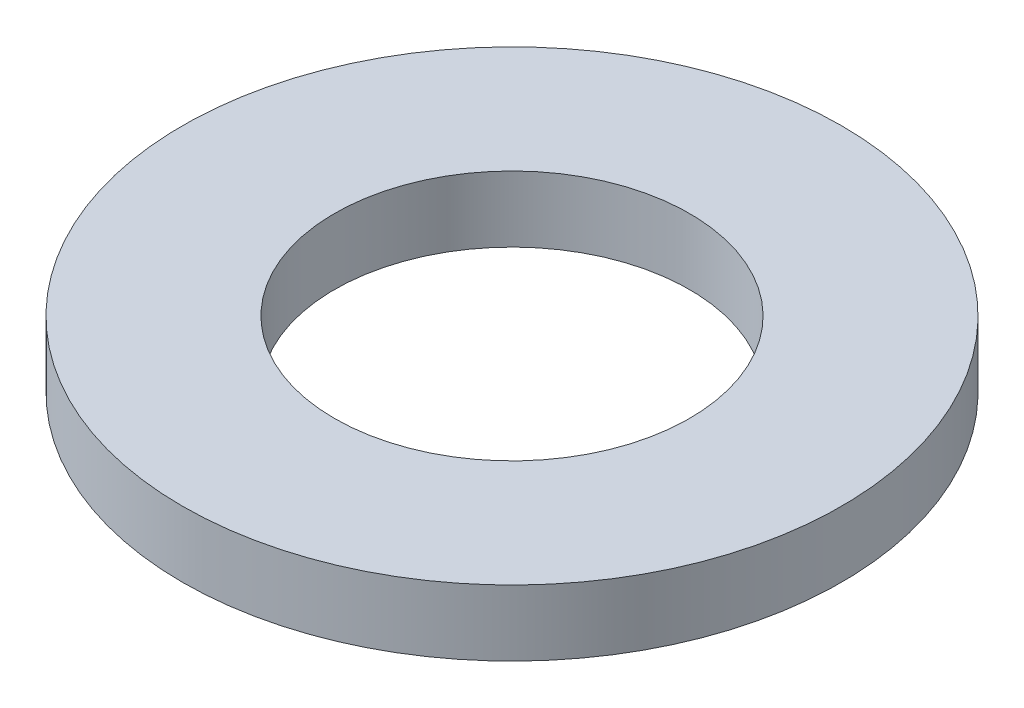
SolidWorks part; units mm, degrees
material "AISI 316 Нержавеющая сталь, лист (SS)"
ref_plane "Спереди" through (0, 0, 0) normal (0, 0, 1) x (1, 0, 0)
ref_plane "Сверху" through (0, 0, 0) normal (0, 1, 0) x (1, 0, 0)
ref_plane "Справа" through (0, 0, 0) normal (1, 0, 0) x (0, 0, -1)
sketch "Эскиз1" plane through (0, 0, 0) normal (0, 1, 0) x (1, 0, 0)
  circle A0 centre (0, 0) radius 4.31
  circle A1 centre (0, 0) radius 8
  dimension "D1" = 8.62
  dimension "D2" = 16
extrude "Бобышка-Вытянуть1" add sketch "Эскиз1" along normal blind 1.6
